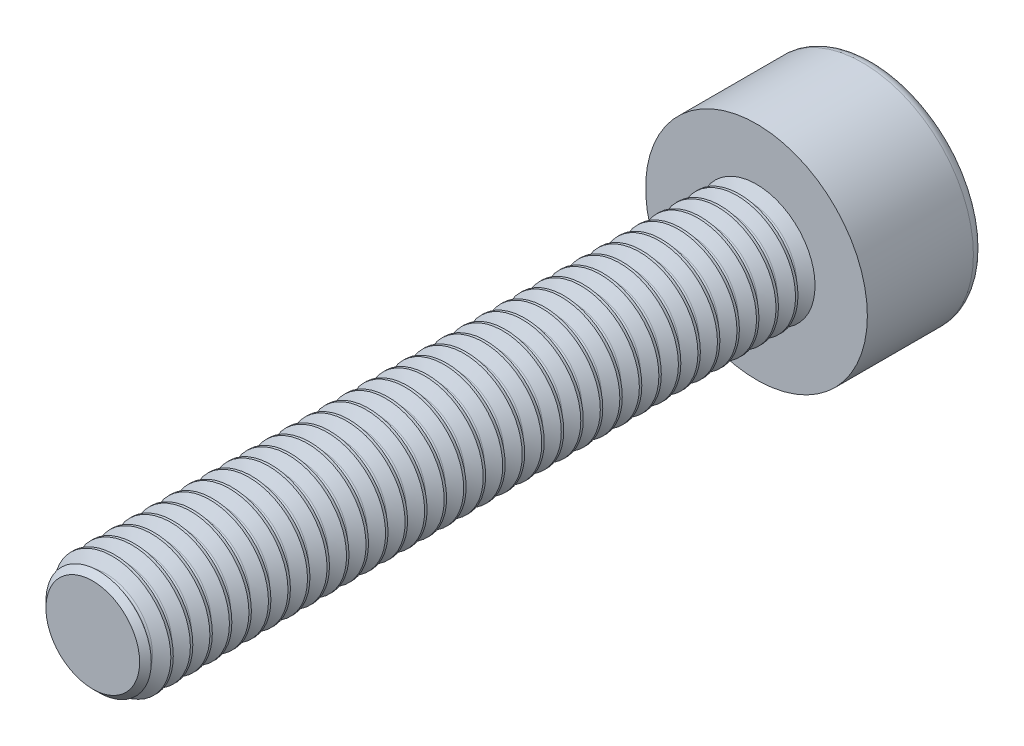
SolidWorks part; units mm, degrees
ref_plane "Front Plane" through (0, 0, 0) normal (0, 0, 1) x (1, 0, 0)
ref_plane "Top Plane" through (0, 0, 0) normal (0, 1, 0) x (1, 0, 0)
ref_plane "Right Plane" through (0, 0, 0) normal (1, 0, 0) x (0, 0, -1)
ref_plane "Plane1" through (0, 0, 0) normal (0, -1, 0) x (1, 0, 0)
sketch "Sketch1" plane through (0, 0, 0) normal (0, -1, 0) x (1, 0, 0)
  line L1 (0, -3) -> (0, 17)
  line L2 (0, -3) -> (2.84, -3)
  line L3 (2.84, -3) -> (2.84, 0)
  line L4 (2.84, 0) -> (1.5, 0)
  line L5 (1.5, 0) -> (1.2023, 0.1719)
  line L6 (1.2023, 0.2656) -> (1.5, 0.4375)
  line L7 (1.5, 0.4375) -> (1.5, 0.5)
  line L8 (1.5, 0.5) -> (1.2023, 0.6719)
  line L9 (1.2023, 0.7656) -> (1.5, 0.9375)
  line L10 (1.5, 0.9375) -> (1.5, 1)
  line L11 (1.5, 1) -> (1.2023, 1.1719)
  line L12 (1.2023, 1.2656) -> (1.5, 1.4375)
  line L13 (1.5, 1.4375) -> (1.5, 1.5)
  line L14 (1.5, 1.5) -> (1.2023, 1.6719)
  line L15 (1.2023, 1.7656) -> (1.5, 1.9375)
  line L16 (1.5, 1.9375) -> (1.5, 2)
  line L17 (1.5, 2) -> (1.2023, 2.1719)
  line L18 (1.2023, 2.2656) -> (1.5, 2.4375)
  line L19 (1.5, 2.4375) -> (1.5, 2.5)
  line L20 (1.5, 2.5) -> (1.2023, 2.6719)
  line L21 (1.2023, 2.7656) -> (1.5, 2.9375)
  line L22 (1.5, 2.9375) -> (1.5, 3)
  line L23 (1.5, 3) -> (1.2023, 3.1719)
  line L24 (1.2023, 3.2656) -> (1.5, 3.4375)
  line L25 (1.5, 3.4375) -> (1.5, 3.5)
  line L26 (1.5, 3.5) -> (1.2023, 3.6719)
  line L27 (1.2023, 3.7656) -> (1.5, 3.9375)
  line L28 (1.5, 3.9375) -> (1.5, 4)
  line L29 (1.5, 4) -> (1.2023, 4.1719)
  line L30 (1.2023, 4.2656) -> (1.5, 4.4375)
  line L31 (1.5, 4.4375) -> (1.5, 4.5)
  line L32 (1.5, 4.5) -> (1.2023, 4.6719)
  line L33 (1.2023, 4.7656) -> (1.5, 4.9375)
  line L34 (1.5, 4.9375) -> (1.5, 5)
  line L35 (1.5, 5) -> (1.2023, 5.1719)
  line L36 (1.2023, 5.2656) -> (1.5, 5.4375)
  line L37 (1.5, 5.4375) -> (1.5, 5.5)
  line L38 (1.5, 5.5) -> (1.2023, 5.6719)
  line L39 (1.2023, 5.7656) -> (1.5, 5.9375)
  line L40 (1.5, 5.9375) -> (1.5, 6)
  line L41 (1.5, 6) -> (1.2023, 6.1719)
  line L42 (1.2023, 6.2656) -> (1.5, 6.4375)
  line L43 (1.5, 6.4375) -> (1.5, 6.5)
  line L44 (1.5, 6.5) -> (1.2023, 6.6719)
  line L45 (1.2023, 6.7656) -> (1.5, 6.9375)
  line L46 (1.5, 6.9375) -> (1.5, 7)
  line L47 (1.5, 7) -> (1.2023, 7.1719)
  line L48 (1.2023, 7.2656) -> (1.5, 7.4375)
  line L49 (1.5, 7.4375) -> (1.5, 7.5)
  line L50 (1.5, 7.5) -> (1.2023, 7.6719)
  line L51 (1.2023, 7.7656) -> (1.5, 7.9375)
  line L52 (1.5, 7.9375) -> (1.5, 8)
  line L53 (1.5, 8) -> (1.2023, 8.1719)
  line L54 (1.2023, 8.2656) -> (1.5, 8.4375)
  line L55 (1.5, 8.4375) -> (1.5, 8.5)
  line L56 (1.5, 8.5) -> (1.2023, 8.6719)
  line L57 (1.2023, 8.7656) -> (1.5, 8.9375)
  line L58 (1.5, 8.9375) -> (1.5, 9)
  line L59 (1.5, 9) -> (1.2023, 9.1719)
  line L60 (1.2023, 9.2656) -> (1.5, 9.4375)
  line L61 (1.5, 9.4375) -> (1.5, 9.5)
  line L62 (1.5, 9.5) -> (1.2023, 9.6719)
  line L63 (1.2023, 9.7656) -> (1.5, 9.9375)
  line L64 (1.5, 9.9375) -> (1.5, 10)
  line L65 (1.5, 10) -> (1.2023, 10.1719)
  line L66 (1.2023, 10.2656) -> (1.5, 10.4375)
  line L67 (1.5, 10.4375) -> (1.5, 10.5)
  line L68 (1.5, 10.5) -> (1.2023, 10.6719)
  line L69 (1.2023, 10.7656) -> (1.5, 10.9375)
  line L70 (1.5, 10.9375) -> (1.5, 11)
  line L71 (1.5, 11) -> (1.2023, 11.1719)
  line L72 (1.2023, 11.2656) -> (1.5, 11.4375)
  line L73 (1.5, 11.4375) -> (1.5, 11.5)
  line L74 (1.5, 11.5) -> (1.2023, 11.6719)
  line L75 (1.2023, 11.7656) -> (1.5, 11.9375)
  line L76 (1.5, 11.9375) -> (1.5, 12)
  line L77 (1.5, 12) -> (1.2023, 12.1719)
  line L78 (1.2023, 12.2656) -> (1.5, 12.4375)
  line L79 (1.5, 12.4375) -> (1.5, 12.5)
  line L80 (1.5, 12.5) -> (1.2023, 12.6719)
  line L81 (1.2023, 12.7656) -> (1.5, 12.9375)
  line L82 (1.5, 12.9375) -> (1.5, 13)
  line L83 (1.5, 13) -> (1.2023, 13.1719)
  line L84 (1.2023, 13.2656) -> (1.5, 13.4375)
  line L85 (1.5, 13.4375) -> (1.5, 13.5)
  line L86 (1.5, 13.5) -> (1.2023, 13.6719)
  line L87 (1.2023, 13.7656) -> (1.5, 13.9375)
  line L88 (1.5, 13.9375) -> (1.5, 14)
  line L89 (1.5, 14) -> (1.2023, 14.1719)
  line L90 (1.2023, 14.2656) -> (1.5, 14.4375)
  line L92 (1.5, 16.5) -> (1.2023, 16.6719)
  line L93 (1.2023, 16.7656) -> (1.3494, 16.8506)
  line L94 (1.3494, 16.8506) -> (1.2, 17)
  line L95 (1.5, 14.5) -> (1.2023, 14.6719)
  line L96 (1.5, 14.4375) -> (1.5, 14.5)
  line L97 (1.2023, 14.7656) -> (1.5, 14.9375)
  line L98 (1.5, 16) -> (1.2023, 16.1719)
  line L99 (1.5, 14.9375) -> (1.5, 15)
  line L100 (1.2023, 15.7656) -> (1.5, 15.9375)
  line L101 (1.5, 15.4375) -> (1.5, 15.5)
  line L102 (1.2023, 16.2656) -> (1.5, 16.4375)
  line L103 (1.5, 15.9375) -> (1.5, 16)
  line L104 (1.2023, 15.2656) -> (1.5, 15.4375)
  line L105 (1.5, 15.5) -> (1.2023, 15.6719)
  line L106 (1.5, 15) -> (1.2023, 15.1719)
  line L107 (1.5, 16.4375) -> (1.5, 16.5)
  line L108 (1.5, 13.9375) -> (1.5, 16.5) construction
  line L109 (1.2, 17) -> (0, 17)
  spline S0 degree 3 poles (1.1752, 0.2188) (1.1752, 0.2007) (1.1867, 0.1809) (1.2023, 0.1719) knots 0 0 0 0 1 1 1 1
  spline S1 degree 3 poles (1.2023, 0.2656) (1.1867, 0.2566) (1.1752, 0.2368) (1.1752, 0.2188) knots 0 0 0 0 1 1 1 1
  spline S2 degree 3 poles (1.2023, 0.6719) (1.1867, 0.6809) (1.1752, 0.7007) (1.1752, 0.7188) knots 0 0 0 0 1 1 1 1
  spline S3 degree 3 poles (1.1752, 0.7188) (1.1752, 0.7368) (1.1867, 0.7566) (1.2023, 0.7656) knots 0 0 0 0 1 1 1 1
  spline S4 degree 3 poles (1.2023, 1.1719) (1.1867, 1.1809) (1.1752, 1.2007) (1.1752, 1.2188) knots 0 0 0 0 1 1 1 1
  spline S5 degree 3 poles (1.1752, 1.2188) (1.1752, 1.2368) (1.1867, 1.2566) (1.2023, 1.2656) knots 0 0 0 0 1 1 1 1
  spline S6 degree 3 poles (1.2023, 1.6719) (1.1867, 1.6809) (1.1752, 1.7007) (1.1752, 1.7188) knots 0 0 0 0 1 1 1 1
  spline S7 degree 3 poles (1.1752, 1.7188) (1.1752, 1.7368) (1.1867, 1.7566) (1.2023, 1.7656) knots 0 0 0 0 1 1 1 1
  spline S8 degree 3 poles (1.2023, 2.1719) (1.1867, 2.1809) (1.1752, 2.2007) (1.1752, 2.2188) knots 0 0 0 0 1 1 1 1
  spline S9 degree 3 poles (1.1752, 2.2188) (1.1752, 2.2368) (1.1867, 2.2566) (1.2023, 2.2656) knots 0 0 0 0 1 1 1 1
  spline S10 degree 3 poles (1.2023, 2.6719) (1.1867, 2.6809) (1.1752, 2.7007) (1.1752, 2.7188) knots 0 0 0 0 1 1 1 1
  spline S11 degree 3 poles (1.1752, 2.7188) (1.1752, 2.7368) (1.1867, 2.7566) (1.2023, 2.7656) knots 0 0 0 0 1 1 1 1
  spline S12 degree 3 poles (1.2023, 3.1719) (1.1867, 3.1809) (1.1752, 3.2007) (1.1752, 3.2188) knots 0 0 0 0 1 1 1 1
  spline S13 degree 3 poles (1.1752, 3.2188) (1.1752, 3.2368) (1.1867, 3.2566) (1.2023, 3.2656) knots 0 0 0 0 1 1 1 1
  spline S14 degree 3 poles (1.2023, 3.6719) (1.1867, 3.6809) (1.1752, 3.7007) (1.1752, 3.7188) knots 0 0 0 0 1 1 1 1
  spline S15 degree 3 poles (1.1752, 3.7188) (1.1752, 3.7368) (1.1867, 3.7566) (1.2023, 3.7656) knots 0 0 0 0 1 1 1 1
  spline S16 degree 3 poles (1.2023, 4.1719) (1.1867, 4.1809) (1.1752, 4.2007) (1.1752, 4.2188) knots 0 0 0 0 1 1 1 1
  spline S17 degree 3 poles (1.1752, 4.2188) (1.1752, 4.2368) (1.1867, 4.2566) (1.2023, 4.2656) knots 0 0 0 0 1 1 1 1
  spline S18 degree 3 poles (1.2023, 4.6719) (1.1867, 4.6809) (1.1752, 4.7007) (1.1752, 4.7188) knots 0 0 0 0 1 1 1 1
  spline S19 degree 3 poles (1.1752, 4.7188) (1.1752, 4.7368) (1.1867, 4.7566) (1.2023, 4.7656) knots 0 0 0 0 1 1 1 1
  spline S20 degree 3 poles (1.2023, 5.1719) (1.1867, 5.1809) (1.1752, 5.2007) (1.1752, 5.2188) knots 0 0 0 0 1 1 1 1
  spline S21 degree 3 poles (1.1752, 5.2188) (1.1752, 5.2368) (1.1867, 5.2566) (1.2023, 5.2656) knots 0 0 0 0 1 1 1 1
  spline S22 degree 3 poles (1.2023, 5.6719) (1.1867, 5.6809) (1.1752, 5.7007) (1.1752, 5.7188) knots 0 0 0 0 1 1 1 1
  spline S23 degree 3 poles (1.1752, 5.7188) (1.1752, 5.7368) (1.1867, 5.7566) (1.2023, 5.7656) knots 0 0 0 0 1 1 1 1
  spline S24 degree 3 poles (1.2023, 6.1719) (1.1867, 6.1809) (1.1752, 6.2007) (1.1752, 6.2188) knots 0 0 0 0 1 1 1 1
  spline S25 degree 3 poles (1.1752, 6.2188) (1.1752, 6.2368) (1.1867, 6.2566) (1.2023, 6.2656) knots 0 0 0 0 1 1 1 1
  spline S26 degree 3 poles (1.2023, 6.6719) (1.1867, 6.6809) (1.1752, 6.7007) (1.1752, 6.7188) knots 0 0 0 0 1 1 1 1
  spline S27 degree 3 poles (1.1752, 6.7188) (1.1752, 6.7368) (1.1867, 6.7566) (1.2023, 6.7656) knots 0 0 0 0 1 1 1 1
  spline S28 degree 3 poles (1.2023, 7.1719) (1.1867, 7.1809) (1.1752, 7.2007) (1.1752, 7.2188) knots 0 0 0 0 1 1 1 1
  spline S29 degree 3 poles (1.1752, 7.2188) (1.1752, 7.2368) (1.1867, 7.2566) (1.2023, 7.2656) knots 0 0 0 0 1 1 1 1
  spline S30 degree 3 poles (1.2023, 7.6719) (1.1867, 7.6809) (1.1752, 7.7007) (1.1752, 7.7188) knots 0 0 0 0 1 1 1 1
  spline S31 degree 3 poles (1.1752, 7.7188) (1.1752, 7.7368) (1.1867, 7.7566) (1.2023, 7.7656) knots 0 0 0 0 1 1 1 1
  spline S32 degree 3 poles (1.2023, 8.1719) (1.1867, 8.1809) (1.1752, 8.2007) (1.1752, 8.2188) knots 0 0 0 0 1 1 1 1
  spline S33 degree 3 poles (1.1752, 8.2188) (1.1752, 8.2368) (1.1867, 8.2566) (1.2023, 8.2656) knots 0 0 0 0 1 1 1 1
  spline S34 degree 3 poles (1.2023, 8.6719) (1.1867, 8.6809) (1.1752, 8.7007) (1.1752, 8.7188) knots 0 0 0 0 1 1 1 1
  spline S35 degree 3 poles (1.1752, 8.7188) (1.1752, 8.7368) (1.1867, 8.7566) (1.2023, 8.7656) knots 0 0 0 0 1 1 1 1
  spline S36 degree 3 poles (1.2023, 9.1719) (1.1867, 9.1809) (1.1752, 9.2007) (1.1752, 9.2188) knots 0 0 0 0 1 1 1 1
  spline S37 degree 3 poles (1.1752, 9.2188) (1.1752, 9.2368) (1.1867, 9.2566) (1.2023, 9.2656) knots 0 0 0 0 1 1 1 1
  spline S38 degree 3 poles (1.2023, 9.6719) (1.1867, 9.6809) (1.1752, 9.7007) (1.1752, 9.7188) knots 0 0 0 0 1 1 1 1
  spline S39 degree 3 poles (1.1752, 9.7188) (1.1752, 9.7368) (1.1867, 9.7566) (1.2023, 9.7656) knots 0 0 0 0 1 1 1 1
  spline S40 degree 3 poles (1.2023, 10.1719) (1.1867, 10.1809) (1.1752, 10.2007) (1.1752, 10.2188) knots 0 0 0 0 1 1 1 1
  spline S41 degree 3 poles (1.1752, 10.2188) (1.1752, 10.2368) (1.1867, 10.2566) (1.2023, 10.2656) knots 0 0 0 0 1 1 1 1
  spline S42 degree 3 poles (1.2023, 10.6719) (1.1867, 10.6809) (1.1752, 10.7007) (1.1752, 10.7188) knots 0 0 0 0 1 1 1 1
  spline S43 degree 3 poles (1.1752, 10.7188) (1.1752, 10.7368) (1.1867, 10.7566) (1.2023, 10.7656) knots 0 0 0 0 1 1 1 1
  spline S44 degree 3 poles (1.2023, 11.1719) (1.1867, 11.1809) (1.1752, 11.2007) (1.1752, 11.2188) knots 0 0 0 0 1 1 1 1
  spline S45 degree 3 poles (1.1752, 11.2188) (1.1752, 11.2368) (1.1867, 11.2566) (1.2023, 11.2656) knots 0 0 0 0 1 1 1 1
  spline S46 degree 3 poles (1.2023, 11.6719) (1.1867, 11.6809) (1.1752, 11.7007) (1.1752, 11.7188) knots 0 0 0 0 1 1 1 1
  spline S47 degree 3 poles (1.1752, 11.7188) (1.1752, 11.7368) (1.1867, 11.7566) (1.2023, 11.7656) knots 0 0 0 0 1 1 1 1
  spline S48 degree 3 poles (1.2023, 12.1719) (1.1867, 12.1809) (1.1752, 12.2007) (1.1752, 12.2188) knots 0 0 0 0 1 1 1 1
  spline S49 degree 3 poles (1.1752, 12.2188) (1.1752, 12.2368) (1.1867, 12.2566) (1.2023, 12.2656) knots 0 0 0 0 1 1 1 1
  spline S50 degree 3 poles (1.2023, 12.6719) (1.1867, 12.6809) (1.1752, 12.7007) (1.1752, 12.7188) knots 0 0 0 0 1 1 1 1
  spline S51 degree 3 poles (1.1752, 12.7188) (1.1752, 12.7368) (1.1867, 12.7566) (1.2023, 12.7656) knots 0 0 0 0 1 1 1 1
  spline S52 degree 3 poles (1.2023, 13.1719) (1.1867, 13.1809) (1.1752, 13.2007) (1.1752, 13.2188) knots 0 0 0 0 1 1 1 1
  spline S53 degree 3 poles (1.1752, 13.2188) (1.1752, 13.2368) (1.1867, 13.2566) (1.2023, 13.2656) knots 0 0 0 0 1 1 1 1
  spline S54 degree 3 poles (1.2023, 13.6719) (1.1867, 13.6809) (1.1752, 13.7007) (1.1752, 13.7188) knots 0 0 0 0 1 1 1 1
  spline S55 degree 3 poles (1.1752, 13.7188) (1.1752, 13.7368) (1.1867, 13.7566) (1.2023, 13.7656) knots 0 0 0 0 1 1 1 1
  spline S56 degree 3 poles (1.2023, 14.1719) (1.1867, 14.1809) (1.1752, 14.2007) (1.1752, 14.2188) knots 0 0 0 0 1 1 1 1
  spline S57 degree 3 poles (1.1752, 14.2188) (1.1752, 14.2368) (1.1867, 14.2566) (1.2023, 14.2656) knots 0 0 0 0 1 1 1 1
  spline S58 degree 3 poles (1.1752, 16.7187) (1.1752, 16.7007) (1.1867, 16.6809) (1.2023, 16.6719) knots 0 0 0 0 1 1 1 1
  spline S59 degree 3 poles (1.2023, 16.7656) (1.1867, 16.7566) (1.1752, 16.7368) (1.1752, 16.7187) knots 0 0 0 0 1 1 1 1
  spline S60 degree 3 poles (1.2023, 14.6719) (1.1867, 14.6809) (1.1752, 14.7007) (1.1752, 14.7188) knots 0 0 0 0 1 1 1 1
  spline S61 degree 3 poles (1.1752, 14.7188) (1.1752, 14.7368) (1.1867, 14.7566) (1.2023, 14.7656) knots 0 0 0 0 1 1 1 1
  spline S62 degree 3 poles (1.1752, 15.2188) (1.1752, 15.2368) (1.1867, 15.2566) (1.2023, 15.2656) knots 0 0 0 0 1 1 1 1
  spline S63 degree 3 poles (1.2023, 15.6719) (1.1867, 15.6809) (1.1752, 15.7007) (1.1752, 15.7188) knots 0 0 0 0 1 1 1 1
  spline S64 degree 3 poles (1.2023, 15.1719) (1.1867, 15.1809) (1.1752, 15.2007) (1.1752, 15.2188) knots 0 0 0 0 1 1 1 1
  spline S65 degree 3 poles (1.1752, 15.7188) (1.1752, 15.7368) (1.1867, 15.7566) (1.2023, 15.7656) knots 0 0 0 0 1 1 1 1
  spline S66 degree 3 poles (1.1752, 16.2188) (1.1752, 16.2368) (1.1867, 16.2566) (1.2023, 16.2656) knots 0 0 0 0 1 1 1 1
  spline S67 degree 3 poles (1.2023, 16.1719) (1.1867, 16.1809) (1.1752, 16.2007) (1.1752, 16.2188) knots 0 0 0 0 1 1 1 1
  dimension "D1" = 2.84
  dimension "D2" = 3
  dimension "D3" = 20
  dimension "D4" = 1.2
  dimension "D5" = 1.5
  dimension "D6" = 0.5
  dimension "D7" = 1.34
  dimension "D8" = 1.3494
revolve "Revolve1" add sketch "Sketch1" angle 360 about L1
sketch "Sketch2" plane through (0, 0, -3) normal (0, 0, -1) x (-1, 0, 0)
  line L0 (-1.4434, 0) -> (-0.7217, -1.25)
  line L1 (-0.7217, -1.25) -> (0.7217, -1.25)
  line L2 (0.7217, -1.25) -> (1.4434, 0)
  line L3 (1.4434, 0) -> (0.7217, 1.25)
  line L4 (0.7217, 1.25) -> (-0.7217, 1.25)
  line L5 (-0.7217, 1.25) -> (-1.4434, 0)
extrude "Cut-Extrude1" cut sketch "Sketch2" against normal blind 1.5
fillet "Fillet1" radius 0.284 1 edges at (2.84, 0, -3)
